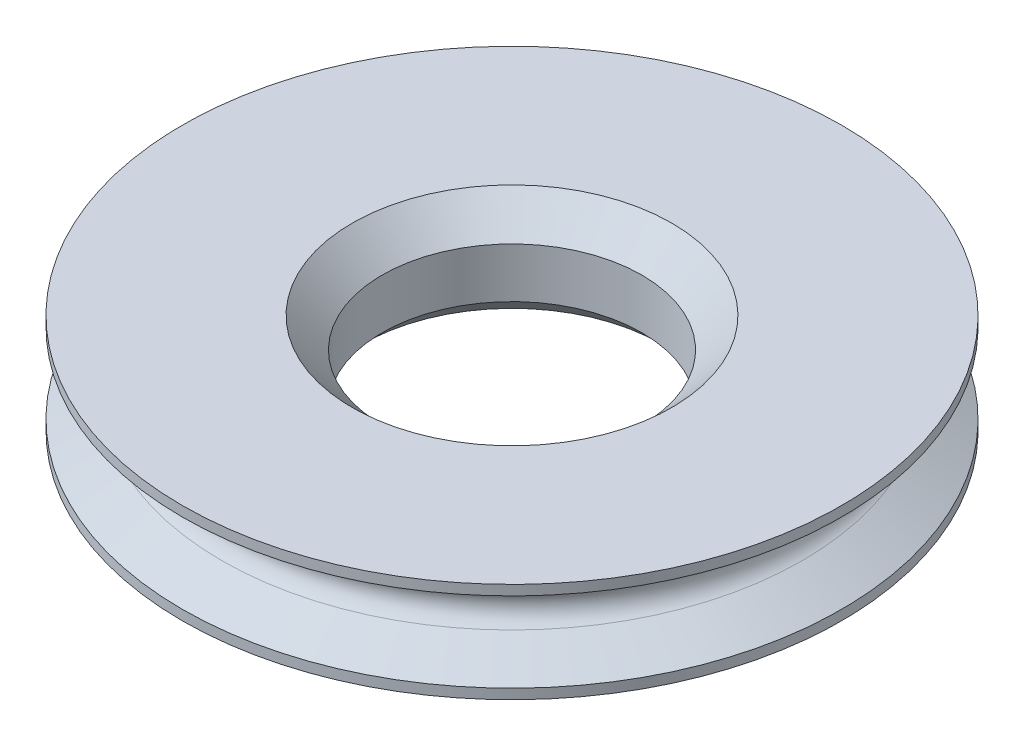
SolidWorks part; units mm, degrees
ref_plane "Front Plane" through (0, 0, 0) normal (0, 0, 1) x (1, 0, 0)
ref_plane "Top Plane" through (0, 0, 0) normal (0, 1, 0) x (1, 0, 0)
ref_plane "Right Plane" through (0, 0, 0) normal (1, 0, 0) x (0, 0, -1)
sketch "Sketch1" plane through (0, 0, 0) normal (0, 0, 1) x (1, 0, 0)
  line L1 (0, 0) -> (22.86, 0)
  line L2 (0, 0) -> (0, 1.27)
  line L3 (0, 12.7) -> (21.59, 12.7)
  line L9 (0, 11.43) -> (0, 12.7)
  line L10 (21.59, 12.7) -> (25.4, 8.89)
  line L13 (22.86, 0) -> (25.4, 2.54)
  line L15 (4.9888, 4.1503) -> (0, 1.27)
  line L16 (4.9888, 8.5497) -> (0, 11.43)
  line L27 (25.4, 8.89) -> (25.4, 2.54)
  line L37 (41.91, 0) -> (41.91, 12.7) construction
  arc A2 (4.9888, 4.1503) -> (4.9888, 8.5497) centre (3.7188, 6.35) ccw
  point P1 (0, 0)
  point P3 (0, 0)
  point P5 (0, 0)
  point P7 (0, 0)
  point P9 (0, 0)
  point P10 (6.2588, 6.35)
  point P23 (41.91, 6.35)
  dimension "D3" = 60
  dimension "D11" = 1.27
  dimension "D13" = 2.54
  dimension "D4" = 12.7
  dimension "D2" = 16.51
  dimension "D5" = 41.91
  dimension "D6" = 45
  dimension "D7" = 2.54
  dimension "D8" = 3.81
  dimension "D9" = 45
  dimension "D10" = 19.05
  dimension "D12" = 1.27
  dimension "D14" = 20.32
revolve "Revolve3" add sketch "Sketch1" angle 360 about L37
